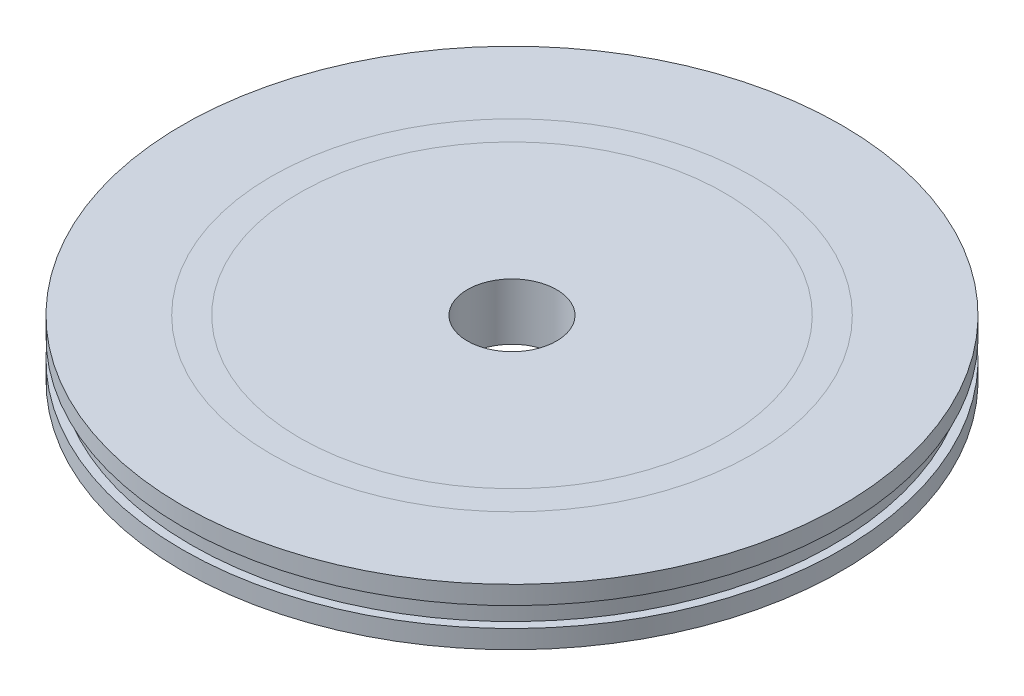
SolidWorks part; units mm, degrees
material "6061-T6 (SS)"
ref_plane "X-Y Datum" through (0, 0, 0) normal (0, 0, 1) x (1, 0, 0)
ref_plane "X-Z Datum" through (0, 0, 0) normal (0, 1, 0) x (1, 0, 0)
ref_plane "Y-Z Datum" through (0, 0, 0) normal (1, 0, 0) x (0, 0, -1)
sketch "Sketch1" plane through (0, 0, 0) normal (1, 0, 0) x (0, 0, -1)
  line L0 (0, 0) -> (0, -32027.2037) construction
  line L1 (0, 0) -> (0, -5.08)
  line L2 (0, -5.08) -> (-29.5656, -5.08)
  line L3 (-29.5656, -5.08) -> (-29.5656, -3.429)
  line L4 (-29.5656, -3.429) -> (-28.8036, -3.429)
  line L5 (-28.8036, -3.429) -> (-28.8036, -1.651)
  line L6 (-28.8036, -1.651) -> (-29.5656, -1.651)
  line L7 (-29.5656, -1.651) -> (-29.5656, 0)
  line L8 (-29.5656, 0) -> (0, 0)
  point P5 (-29.5656, -0.8255)
  dimension "D1" = 29.5656
  dimension "D2" = 5.08
  dimension "D3" = 1.778
  dimension "D4" = 1.651
  dimension "D5" = 0.762
revolve "Revolve1" add sketch "Sketch1" angle 360 about L0
sketch "Sketch2" plane through (0, 0, 0) normal (0, 1, 0) x (1, 0, 0)
  circle A0 centre (0, 0) radius 19.05
  dimension "D1" = 38.1
split line "Split Line1"
sketch "Sketch3" plane through (0, 0, 0) normal (0, 1, 0) x (1, 0, 0)
  circle A0 centre (0, 0) radius 21.59
  dimension "D1" = 43.18
split line "Split Line2"
hole_wizard "Ø8.0mm Dowel Hole1" positions "Sketch4" profile "Sketch5" hole size "Ø8.0" standard "ANSI Metric" end condition through all
sketch "Sketch4" plane through (0, 0, 0) normal (0, 1, 0) x (1, 0, 0)
  point P0 (0, 0)
sketch "Sketch5" plane through (0, 0, 0) normal (1, 0, 0) x (0, 0, 1)
  line L0 (0, 0) -> (0, 5.08)
  line L1 (0, 5.08) -> (4, 5.08)
  line L2 (4, 5.08) -> (4, 0)
  line L5 (4, 0) -> (0, 0)
  line L11 (0, -6.35) -> (0, 107.95) construction
  dimension "Thru Hole Dia." = 8
  dimension "Thru Hole Depth" = 5.08
